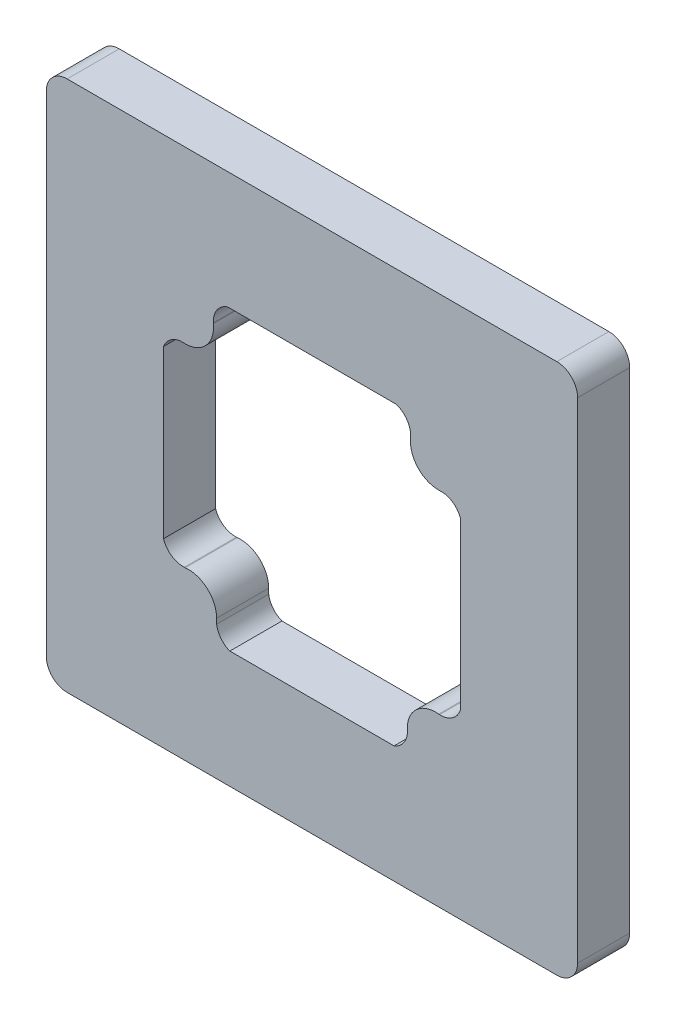
SolidWorks part; units mm, degrees
material "Cedar"
ref_plane "Plan de face" through (0, 0, 0) normal (0, 0, 1) x (1, 0, 0)
ref_plane "Plan de dessus" through (0, 0, 0) normal (0, 1, 0) x (1, 0, 0)
ref_plane "Plan de droite" through (0, 0, 0) normal (1, 0, 0) x (0, 0, -1)
sketch "Sketch1" plane through (0, 0, 0) normal (0, 0, 1) x (1, 0, 0)
  line L0 (-18.9358, 24.3351) -> (-18.9358, 24.5)
  line L1 (-47, 51) -> (47, 51)
  line L2 (-51, 47) -> (-51, -47)
  line L3 (-47, -51) -> (47, -51)
  line L4 (51, 47) -> (51, -47)
  line L5 (-51, 51) -> (-49.8284, 49.8284) construction
  line L6 (-51, -51) -> (-49.8284, -49.8284) construction
  line L7 (-16.1929, 28.5) -> (16.1929, 28.5)
  line L8 (-28.5, 15.7643) -> (-28.5, -16.1929)
  line L9 (-15.7643, -28.5) -> (15.7643, -28.5)
  line L10 (28.5, 15.7643) -> (28.5, -16.1929)
  line L11 (-20.1976, -20.1976) -> (20.1976, 20.1976) construction
  line L12 (-20.1976, 20.1976) -> (-28.5, 28.5) construction
  line L15 (-25.3143, 18.3001) -> (-24.3143, 18.3001)
  line L16 (-20.1976, -20.1976) -> (20.1976, 20.1976) construction
  line L17 (0, -0.5) -> (36.2572, -0.5) construction
  line L18 (18.3001, -25.3143) -> (18.3001, -24.3143)
  line L19 (24.3351, -18.9358) -> (24.5, -18.9358)
  line L20 (0, -0.5) -> (0, 48.9012) construction
  line L21 (-20.1976, 20.1976) -> (20.1976, -20.1976) construction
  line L22 (-20.1976, 20.1976) -> (20.1976, -20.1976) construction
  line L23 (25.3143, 18.3001) -> (24.3143, 18.3001)
  line L24 (18.9358, 24.3351) -> (18.9358, 24.5)
  line L27 (-24.3351, -18.9358) -> (-24.5, -18.9358)
  line L28 (-18.3001, -25.3143) -> (-18.3001, -24.3143)
  line L29 (27.1141, 27.1141) -> (28.5, 28.5) construction
  line L30 (27.1141, 27.1141) -> (51, 51) construction
  line L31 (49.8284, -49.8284) -> (51, -51) construction
  arc A0 (-51, -47) -> (-47, -51) centre (-47, -47) ccw
  arc A1 (47, -51) -> (51, -47) centre (47, -47) ccw
  arc A2 (-47, 51) -> (-51, 47) centre (-47, 47) ccw
  arc A3 (47, 51) -> (51, 47) centre (47, 47) cw
  arc A8 (-16.1929, 28.5) -> (-18.9358, 24.5) centre (-14.9408, 24.701) ccw
  arc A10 (-25.3143, 18.3001) -> (-28.5, 15.7643) centre (-24.7628, 14.3383) ccw
  arc A11 (-24.3143, 18.3001) -> (-18.9358, 24.3351) centre (-24.3143, 23.7143) ccw
  circle A12 centre (-24.3488, 24.3488) radius 2.5 construction
  arc A13 (18.3001, -24.3143) -> (24.3351, -18.9358) centre (23.7143, -24.3143) cw
  arc A14 (18.3001, -25.3143) -> (15.7643, -28.5) centre (14.3383, -24.7628) cw
  arc A15 (28.5, -16.1929) -> (24.5, -18.9358) centre (24.701, -14.9408) cw
  circle A16 centre (24.3488, 24.3488) radius 2.5 construction
  circle A17 centre (24.3488, -25.3488) radius 2.5 construction
  arc A18 (24.3143, 18.3001) -> (18.9358, 24.3351) centre (24.3143, 23.7143) cw
  arc A19 (25.3143, 18.3001) -> (28.5, 15.7643) centre (24.7628, 14.3383) cw
  arc A20 (16.1929, 28.5) -> (18.9358, 24.5) centre (14.9408, 24.701) cw
  circle A21 centre (-24.3488, -25.3488) radius 2.5 construction
  arc A24 (-28.5, -16.1929) -> (-24.5, -18.9358) centre (-24.701, -14.9408) ccw
  arc A25 (-18.3001, -25.3143) -> (-15.7643, -28.5) centre (-14.3383, -24.7628) ccw
  arc A26 (-18.3001, -24.3143) -> (-24.3351, -18.9358) centre (-23.7143, -24.3143) ccw
  point P0 (0, 0)
  point P6 (0, 0)
  dimension "D2" = 4
  dimension "D3" = 5
  dimension "D1" = 102
  dimension "D4" = 57
extrude "Boss-Extrude1" add sketch "Sketch1" along normal mid plane 10
sketch "Sketch2" plane through (0, 0, 5) normal (0, 0, 1) x (1, 0, 0)
  line L0 (-47, -51) -> (47, -51) construction
  line L1 (-51, 47) -> (-51, -47) construction
  line L2 (0, 0) -> (0, -83.0044) construction
  line L3 (-42.0362, 0) -> (92.2906, 0) construction
  circle A0 centre (-17.5, -17.5) radius 2.5
  circle A1 centre (17.5, -17.5) radius 2.5
  circle A2 centre (17.5, 17.5) radius 2.5
  circle A3 centre (-17.5, 17.5) radius 2.5
  dimension "D3" = 5
  dimension "D1" = 33.5
  dimension "D2" = 33.5
extrude "Cut-Extrude1" [suppressed] cut sketch "Sketch2" against normal through all
